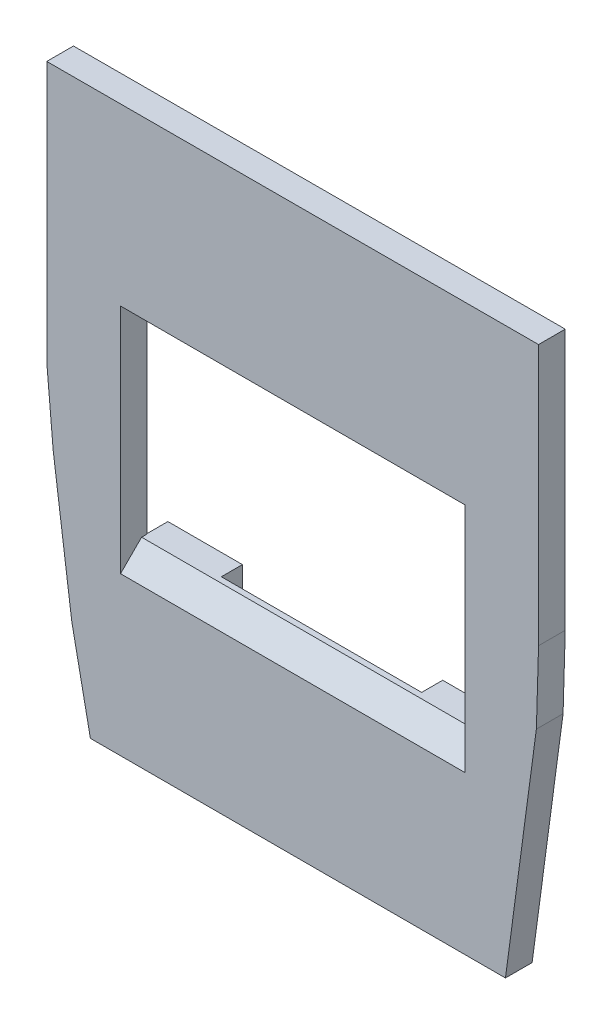
SolidWorks part; units mm, degrees
ref_plane "Front Plane" through (0, 0, 0) normal (0, 0, 1) x (1, 0, 0)
ref_plane "Top Plane" through (0, 0, 0) normal (0, 1, 0) x (1, 0, 0)
ref_plane "Right Plane" through (0, 0, 0) normal (1, 0, 0) x (0, 0, -1)
sketch "Sketch1" plane through (0, 0, 0) normal (0, 0, 1) x (1, 0, 0)
  line L0 (5.4712, 20.6763) -> (40.4712, 20.7265)
  line L1 (5.4712, 20.6763) -> (5.4712, 2.1647)
  line L2 (5.4712, 2.1647) -> (5.9268, -3.0533)
  line L3 (5.9268, -3.0533) -> (7.252, -12.951)
  line L4 (7.252, -12.951) -> (8.5772, -19.4942)
  line L5 (8.5772, -19.4942) -> (37.5772, -19.4942)
  line L16 (38.1156, -19.4942) -> (37.5772, -19.4942)
  line L19 (22.9712, 20.7014) -> (22.9712, -26.335) construction
  line L20 (40.4712, 20.7265) -> (40.4712, 2.1647)
  line L21 (38.1156, -19.4942) -> (39.0061, -12.8429)
  line L22 (39.0061, -12.8429) -> (40.3169, -3.0533)
  line L23 (40.3169, -3.0533) -> (40.4712, 2.1647)
  line L24 (5.4712, 23.379) -> (10.7212, 23.379) construction
  line L25 (40.4712, 23.379) -> (35.2212, 23.379) construction
  line L26 (10.7212, 24.9964) -> (10.7212, -26.335) construction
  line L27 (45.9889, 20.7265) -> (45.9889, 6.7265) construction
  line L28 (48.8739, 6.7265) -> (48.8739, -6.7735) construction
  line L29 (35.2212, 25.4911) -> (35.2212, -23.2707) construction
  line L30 (53.7943, 6.7265) -> (-4.822, 6.7265) construction
  line L31 (52.5107, -6.7735) -> (-2.3262, -6.7735) construction
  line L35 (10.7212, -6.7735) -> (10.7212, 6.7265)
  line L36 (10.7212, -6.7735) -> (35.2212, -6.7735)
  line L37 (35.2212, -6.7735) -> (35.2212, 6.7265)
  line L38 (35.2212, 6.7265) -> (10.7212, 6.7265)
extrude "Boss-Extrude1" add sketch "Sketch1" along normal blind 1.9
chamfer "Chamfer2" distance 1.5 angle 45 2 edges at (22.9712, 6.7265, 1.9) (22.9712, -6.7735, 1.9)
sketch "Sketch3" plane through (0, 0, 0) normal (0, 0, -1) x (-1, 0, 0)
  line L0 (-10.7212, -6.7735) -> (-35.2212, -6.7735) construction
  line L5 (-35.2212, -6.7735) -> (-30.251, -6.7735)
  line L6 (-35.2212, -6.7735) -> (-35.2212, -11.7735)
  line L7 (-35.2212, -11.7735) -> (-30.251, -11.7735)
  line L8 (-10.6917, -6.7735) -> (-10.6917, -11.7735)
  line L9 (-35.2212, -6.7735) -> (-35.2212, 6.7265) construction
  line L12 (-30.251, -6.7735) -> (-30.251, -11.7735)
  line L13 (-15.9958, -6.7735) -> (-15.9958, -11.7735)
  line L16 (-15.9958, -6.7735) -> (-10.6917, -6.7735)
  line L17 (-15.9958, -11.7735) -> (-10.6917, -11.7735)
  line L18 (-42.9105, 10.7265) -> (-2.8573, 10.4951) construction
  line L20 (-35.2212, 10.6821) -> (-30.251, 10.6821)
  line L21 (-35.2212, 10.6821) -> (-35.2212, 14.6221)
  line L22 (-35.2212, 14.6221) -> (-30.251, 14.6221)
  line L23 (-30.251, 10.6821) -> (-30.251, 14.6221)
  line L24 (-10.6917, 10.5404) -> (-15.9958, 10.5404)
  line L25 (-10.6917, 10.5404) -> (-10.6917, 14.6221)
  line L26 (-10.6917, 14.6221) -> (-15.9958, 14.6221)
  line L27 (-15.9958, 10.5404) -> (-15.9958, 14.6221)
  dimension "D1" = 4
extrude "Boss-Extrude4" add sketch "Sketch3" along normal blind 1.5
